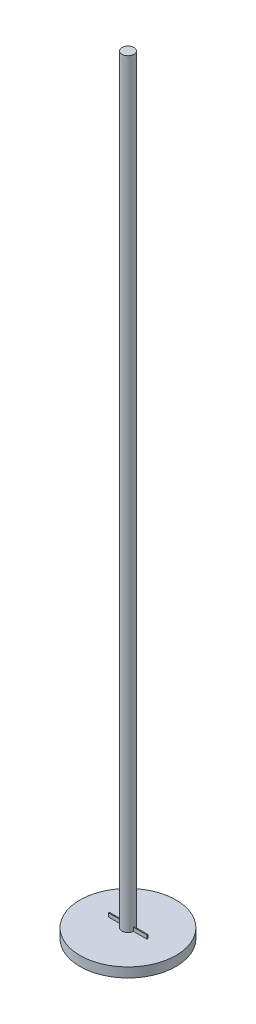
SolidWorks part; units mm, degrees
ref_plane "前视基准面" through (0, 0, 0) normal (0, 0, 1) x (1, 0, 0)
ref_plane "上视基准面" through (0, 0, 0) normal (0, 1, 0) x (1, 0, 0)
ref_plane "右视基准面" through (0, 0, 0) normal (1, 0, 0) x (0, 0, -1)
other "Configuration Table"
sketch "草图1" plane through (0, 0, 0) normal (0, 1, 0) x (1, 0, 0)
  circle A0 centre (0, 0) radius 5
extrude "凸台-拉伸1" add sketch "草图1" along normal blind 1
sketch "草图2" plane through (0, 0, 0) normal (0, 1, 0) x (1, 0, 0)
  circle A0 centre (0, 0) radius 0.6225
extrude "凸台-拉伸2" add sketch "草图2" along normal blind 80
sketch "草图3" plane through (0, 0, 0) normal (0, 0, 1) x (1, 0, 0)
  line L0 (-1.9808, 0) -> (2.0208, 0)
  line L1 (-5, 0) -> (5, 0) construction
  line L2 (2.0208, 0) -> (2.0208, 1.3758)
  line L3 (2.0208, 1.3758) -> (-1.9808, 1.3758)
  line L4 (-1.9808, 1.3758) -> (-1.9808, 0)
extrude "凸台-拉伸3" add sketch "草图3" along normal mid plane 0.1
